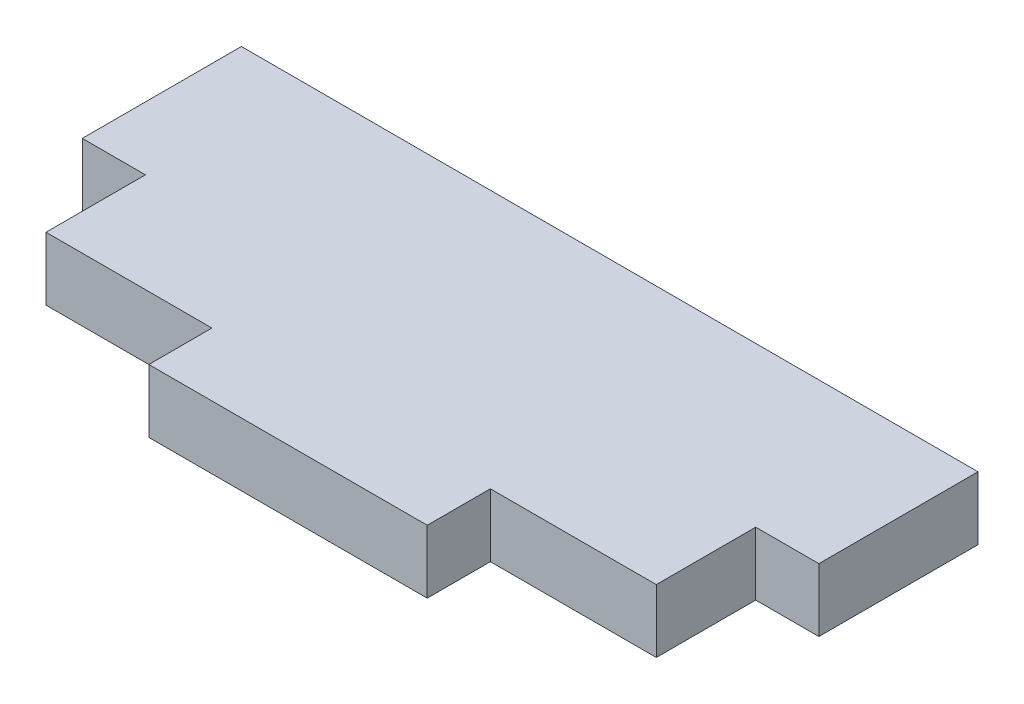
SolidWorks part; units mm, degrees
ref_plane "Front Plane" through (0, 0, 0) normal (0, 0, 1) x (1, 0, 0)
ref_plane "Top Plane" through (0, 0, 0) normal (0, 1, 0) x (1, 0, 0)
ref_plane "Right Plane" through (0, 0, 0) normal (1, 0, 0) x (0, 0, -1)
sketch "Sketch1" plane through (0, 0, 0) normal (0, 1, 0) x (1, 0, 0)
  line L1 (-15.3423, -14.865) -> (15.3423, -14.865)
  line L2 (-15.3423, -14.865) -> (-15.3423, 14.865)
  line L3 (-15.3423, 14.865) -> (15.3423, 14.865)
  line L4 (15.3423, -14.865) -> (15.3423, 14.865)
  line L5 (-15.3423, -14.865) -> (15.3423, 14.865) construction
  line L6 (-15.3423, 14.865) -> (15.3423, -14.865) construction
  line L7 (-15.3423, 9.865) -> (-18.5173, 9.865)
  line L8 (-15.3423, 9.865) -> (-15.3423, 1.865)
  line L9 (-15.3423, 1.865) -> (-18.5173, 1.865)
  line L10 (-18.5173, 9.865) -> (-18.5173, 1.865)
  line L11 (-15.3423, -1.865) -> (-18.5173, -1.865)
  line L12 (-15.3423, -1.865) -> (-15.3423, -9.865)
  line L13 (-15.3423, -9.865) -> (-18.5173, -9.865)
  line L14 (-18.5173, -1.865) -> (-18.5173, -9.865)
  line L15 (15.3423, 9.865) -> (18.5173, 9.865)
  line L16 (15.3423, 9.865) -> (15.3423, 1.865)
  line L17 (15.3423, 1.865) -> (18.5173, 1.865)
  line L18 (18.5173, 9.865) -> (18.5173, 1.865)
  line L19 (15.3423, -1.865) -> (18.5173, -1.865)
  line L20 (15.3423, -1.865) -> (15.3423, -9.865)
  line L21 (15.3423, -9.865) -> (18.5173, -9.865)
  line L22 (18.5173, -1.865) -> (18.5173, -9.865)
  point P0 (0, 0)
  dimension "D1" = 30.6846
  dimension "D2" = 3.175
  dimension "D3" = 3.175
  dimension "D4" = 3.175
  dimension "D5" = 3.175
  dimension "D6" = 29.73
  dimension "D7" = 5
  dimension "D8" = 5
  dimension "D9" = 8
  dimension "D10" = 8
  dimension "D11" = 5
  dimension "D12" = 8
  dimension "D13" = 8
  dimension "D14" = 5
extrude "Boss-Extrude1" add sketch "Sketch1" along normal blind 3.175 contours L7 L10 L9 L2 | L1 L4 L3 L2 | L22 L19 L4 L21 | L18 L15 L4 L17 | L11 L14 L13 L2
sketch "Sketch2" plane through (0, 0, 14.865) normal (0, 0, 1) x (1, 0, 0)
  line L1 (-15.3423, 3.175) -> (15.3423, 3.175)
  line L2 (-15.3423, 3.175) -> (-15.3423, 0)
  line L3 (-15.3423, 0) -> (15.3423, 0)
  line L4 (15.3423, 3.175) -> (15.3423, 0)
  line L5 (-7, 3.175) -> (7, 3.175)
  line L6 (-7, 3.175) -> (-7, 0)
  line L7 (-7, 0) -> (7, 0)
  line L8 (7, 3.175) -> (7, 0)
  dimension "D1" = 7
  dimension "D2" = 14
extrude "Boss-Extrude5" add sketch "Sketch2" along normal blind 3.175 contours L8 L1 L6 L3
sketch "Sketch3" plane through (0, 3.175, 0) normal (0, 1, 0) x (1, 0, 0)
  line L1 (-15.3423, -1.865) -> (22.1545, -1.865)
  line L2 (-15.3423, -1.865) -> (-15.3423, 15.7221)
  line L3 (-15.3423, 15.7221) -> (22.1545, 15.7221)
  line L4 (22.1545, -1.865) -> (22.1545, 15.7221)
  line L5 (-10.2184, -1.865) -> (-23.2997, -1.865)
  line L6 (-10.2184, -1.865) -> (-10.2184, 15.7221)
  line L7 (-10.2184, 15.7221) -> (-23.2997, 15.7221)
  line L8 (-23.2997, -1.865) -> (-23.2997, 15.7221)
  line M1 (-15.3423, 1.865) -> (-15.3423, -1.865)
  line M2 (-15.3423, -1.865) -> (-18.5173, -1.865)
  line M14 (18.5173, -1.865) -> (15.3423, -1.865)
  line M15 (15.3423, -1.865) -> (15.3423, 1.865)
  line M16 (15.3423, 1.865) -> (18.5173, 1.865)
  line M17 (18.5173, 1.865) -> (18.5173, 9.865)
  line M18 (18.5173, 9.865) -> (15.3423, 9.865)
  line M19 (15.3423, 9.865) -> (15.3423, 14.865)
  line M20 (15.3423, 14.865) -> (-15.3423, 14.865)
  line M21 (-15.3423, 14.865) -> (-15.3423, 9.865)
  line M22 (-15.3423, 9.865) -> (-18.5173, 9.865)
  line M23 (-18.5173, 9.865) -> (-18.5173, 1.865)
  line M24 (-18.5173, 1.865) -> (-15.3423, 1.865)
extrude "Cut-Extrude1" cut sketch "Sketch3" against normal up to surface (3.175 mm away) contours L8 L5 L2 L7 M2 M1 M24 M23 M22 M21 | L1 L6 L2 M20 M21 M1 | L6 L1 M15 M16 M17 M18 M19 M20 | L6 L1 L4 L3 M20 M19 M18 M17 M16 M15 M14 | L2 M24 M22 M23 | L6 L3 L2 M20 up to face at (0, 0, 2.7421)
